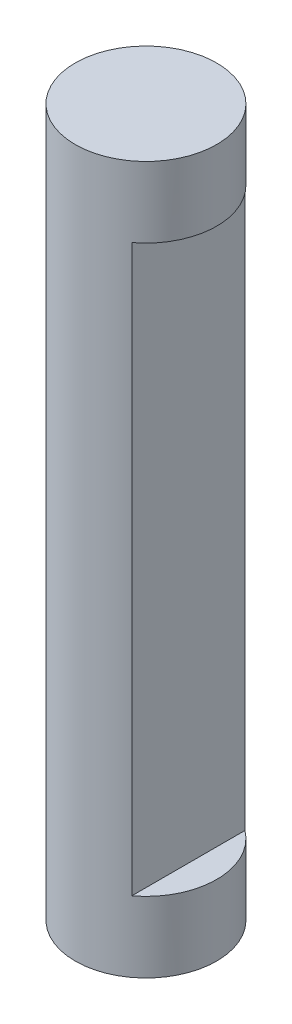
SolidWorks part; units mm, degrees
ref_plane "Front Plane" through (0, 0, 0) normal (0, 0, 1) x (1, 0, 0)
ref_plane "Top Plane" through (0, 0, 0) normal (0, 1, 0) x (1, 0, 0)
ref_plane "Right Plane" through (0, 0, 0) normal (1, 0, 0) x (0, 0, -1)
sketch "Sketch1" plane through (0, 0, 0) normal (0, 1, 0) x (1, 0, 0)
  circle A0 centre (0, 0) radius 50
  dimension "D1" = 100
extrude "Boss-Extrude1" add sketch "Sketch1" along normal blind 500
sketch "Sketch2" plane through (0, 0, 0) normal (0, -1, 0) x (1, 0, 0)
  circle A0 centre (0, 0) radius 25
  dimension "D1" = 50
extrude "Cut-Extrude1" cut sketch "Sketch2" against normal blind 20
ref_plane "Plane1" through (30, 0, 0) normal (1, 0, 0) x (0, 0, -1)
sketch "Sketch3" plane through (30, 0, 0) normal (1, 0, 0) x (0, 0, -1)
  line L0 (0, 0) -> (0, 500) construction
  line L1 (-100, 50) -> (100, 50)
  line L2 (-100, 50) -> (-100, 450)
  line L3 (-100, 450) -> (100, 450)
  line L4 (100, 50) -> (100, 450)
  line L5 (-100, 50) -> (100, 450) construction
  line L6 (-100, 450) -> (100, 50) construction
  line L7 (50, 500) -> (-50, 500) construction
  point P0 (0, 250)
  point P10 (0, 250)
  dimension "D1" = 400
  dimension "D2" = 100
extrude "Cut-Extrude2" cut sketch "Sketch3" along normal blind 50
